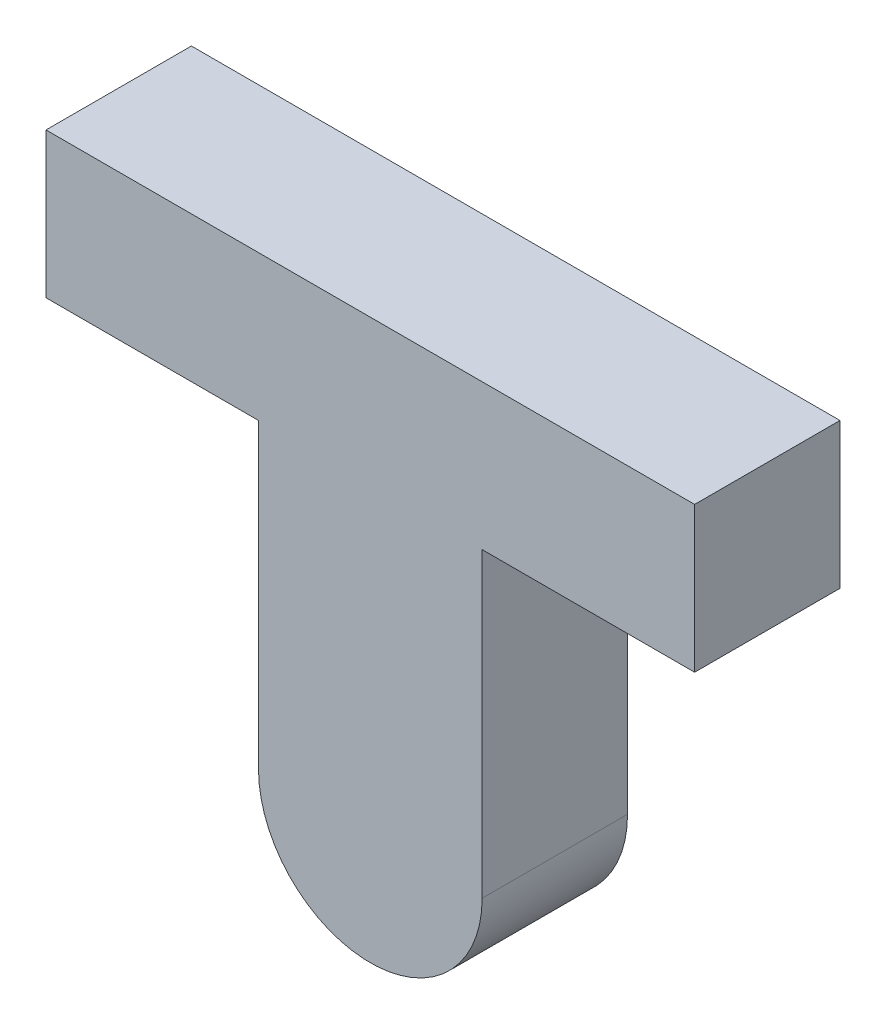
SolidWorks part; units mm, degrees
ref_plane "Front Plane" through (0, 0, 0) normal (0, 0, 1) x (1, 0, 0)
ref_plane "Top Plane" through (0, 0, 0) normal (0, 1, 0) x (1, 0, 0)
ref_plane "Right Plane" through (0, 0, 0) normal (1, 0, 0) x (0, 0, -1)
sketch "Sketch1" plane through (0, 0, 0) normal (0, 0, 1) x (1, 0, 0)
  line L0 (1, 2.7) -> (2.9, 2.7)
  line L2 (-1, 2.7) -> (-1, 0)
  line L4 (1, 2.7) -> (1, 0)
  line L5 (-2.9, 4) -> (2.9, 4)
  line L6 (-2.9, 4) -> (-2.9, 2.7)
  line L7 (-2.9, 2.7) -> (-1, 2.7)
  line L8 (2.9, 4) -> (2.9, 2.7)
  arc A0 (-1, 0) -> (1, 0) centre (0, 0) ccw
  dimension "D1" = 2
  dimension "D2" = 2
  dimension "D4" = 5.8
  dimension "D5" = 1.3
  dimension "D6" = 2.7
extrude "Boss-Extrude1" add sketch "Sketch1" along normal mid plane 1.3
